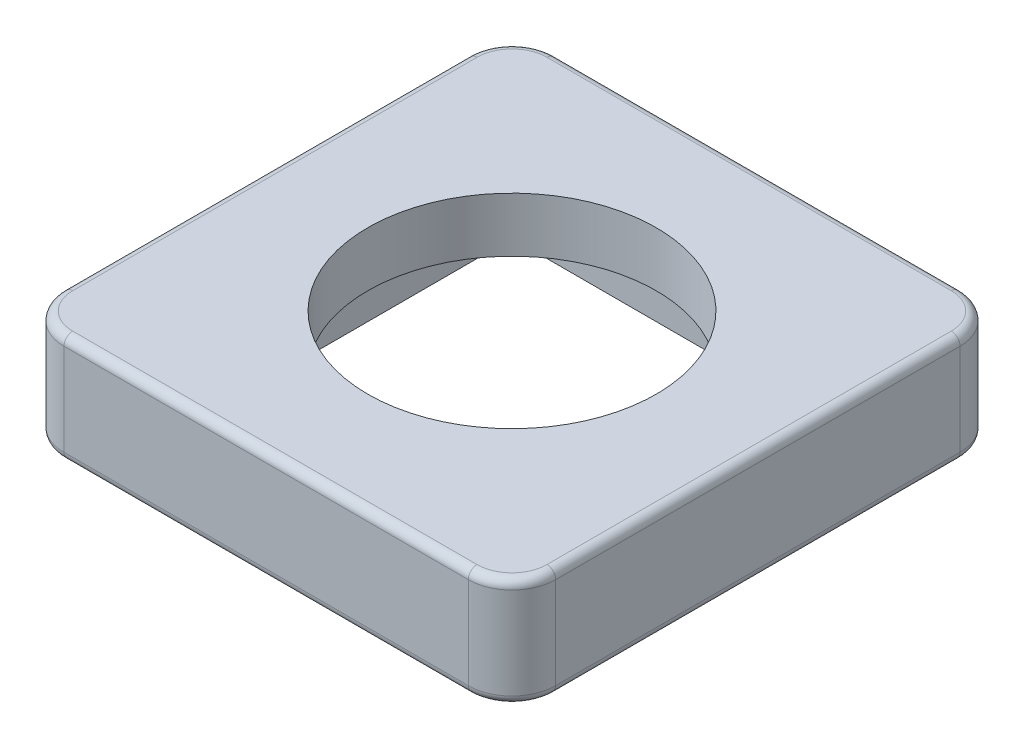
SolidWorks part; units mm, degrees
material "PBT General Purpose"
ref_plane "Front Plane" through (0, 0, 0) normal (0, 0, 1) x (1, 0, 0)
ref_plane "Top Plane" through (0, 0, 0) normal (0, 1, 0) x (1, 0, 0)
ref_plane "Right Plane" through (0, 0, 0) normal (1, 0, 0) x (0, 0, -1)
sketch "Sketch1" plane through (0, 0, 0) normal (0, 1, 0) x (1, 0, 0)
  line L1 (-28.575, -28.575) -> (28.575, -28.575)
  line L2 (-28.575, -28.575) -> (-28.575, 28.575)
  line L3 (-28.575, 28.575) -> (28.575, 28.575)
  line L4 (28.575, -28.575) -> (28.575, 28.575)
  line L5 (-28.575, -28.575) -> (28.575, 28.575) construction
  line L6 (-28.575, 28.575) -> (28.575, -28.575) construction
  point P0 (0, 0)
  dimension "D1" = 57.15
extrude "Boss-Extrude2" add sketch "Sketch1" along normal blind 12.7
fillet "Fillet1" radius 5.08 4 edges at (-28.575, 6.35, 28.575) (28.575, 6.35, 28.575) (28.575, 6.35, -28.575) (-28.575, 6.35, -28.575)
fillet "Fillet2" radius 1.016 16 edges at (-27.0871, 12.7, -27.0871) (0, 12.7, -28.575) (27.0871, 12.7, -27.0871) (28.575, 12.7, 0) (27.0871, 12.7, 27.0871) (0, 12.7, 28.575) (-27.0871, 12.7, 27.0871) (-28.575, 12.7, 0) (-27.0871, 0, -27.0871) (0, 0, -28.575) (27.0871, 0, -27.0871) (28.575, 0, 0) (27.0871, 0, 27.0871) (0, 0, 28.575) (-27.0871, 0, 27.0871) (-28.575, 0, 0)
sketch "Sketch15" plane through (0, 12.7, 0) normal (0, 1, 0) x (1, 0, 0)
  circle A0 centre (0, 0) radius 16.764
extrude "Cut-Extrude1" cut sketch "Sketch15" against normal blind 6.35
sketch "Sketch16" plane through (0, 0, 0) normal (0, -1, 0) x (1, 0, 0)
  line L1 (-20, -20) -> (20, -20)
  line L2 (-20, -20) -> (-20, 20)
  line L3 (-20, 20) -> (20, 20)
  line L4 (20, -20) -> (20, 20)
  line L5 (-20, -20) -> (20, 20) construction
  line L6 (-20, 20) -> (20, -20) construction
  point P0 (0, 0)
extrude "Cut-Extrude2" cut sketch "Sketch16" against normal blind 6.35
